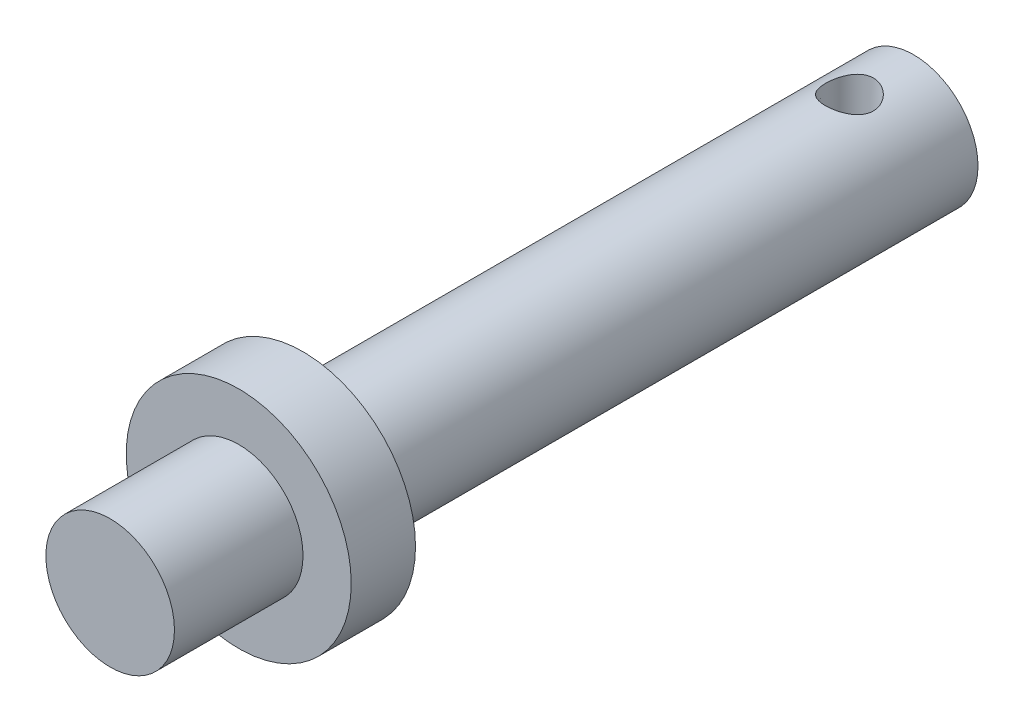
SolidWorks part; units mm, degrees
ref_plane "前视基准面" through (0, 0, 0) normal (0, 0, 1) x (1, 0, 0)
ref_plane "上视基准面" through (0, 0, 0) normal (0, 1, 0) x (1, 0, 0)
ref_plane "右视基准面" through (0, 0, 0) normal (1, 0, 0) x (0, 0, -1)
sketch "草图1" plane through (0, 0, 0) normal (0, 0, 1) x (1, 0, 0)
  circle A0 centre (0, 0) radius 4
  dimension "D1" = 8
extrude "凸台-拉伸1" add sketch "草图1" along normal blind 50
sketch "草图2" plane through (0, 0, 50) normal (0, 0, 1) x (1, 0, 0)
  circle A0 centre (0, 0) radius 7
  dimension "D1" = 14
extrude "凸台-拉伸2" add sketch "草图2" against normal blind 4 from offset 8 offset against normal yes
sketch "草图4" plane through (0, 0, 0) normal (1, 0, 0) x (0, 0, -1)
  line L0 (-4, 6.787) -> (-4, -12.446) construction
  line L1 (0, 7.7) -> (0, -7.7) construction
  line L2 (-2.6, -4.8418) -> (-4, -4.8418)
  line L4 (-2.6, -4.8418) -> (-2.5, 4.7515)
  line L5 (-2.5, 4.7515) -> (-4, 4.7515)
  line L6 (-4, -4.8418) -> (-4, 4.7515)
  dimension "D1" = 4
  dimension "D2" = 1.5
  dimension "D3" = 1.4
revolve "切除-旋转1" cut sketch "草图4" angle 360 about L0
